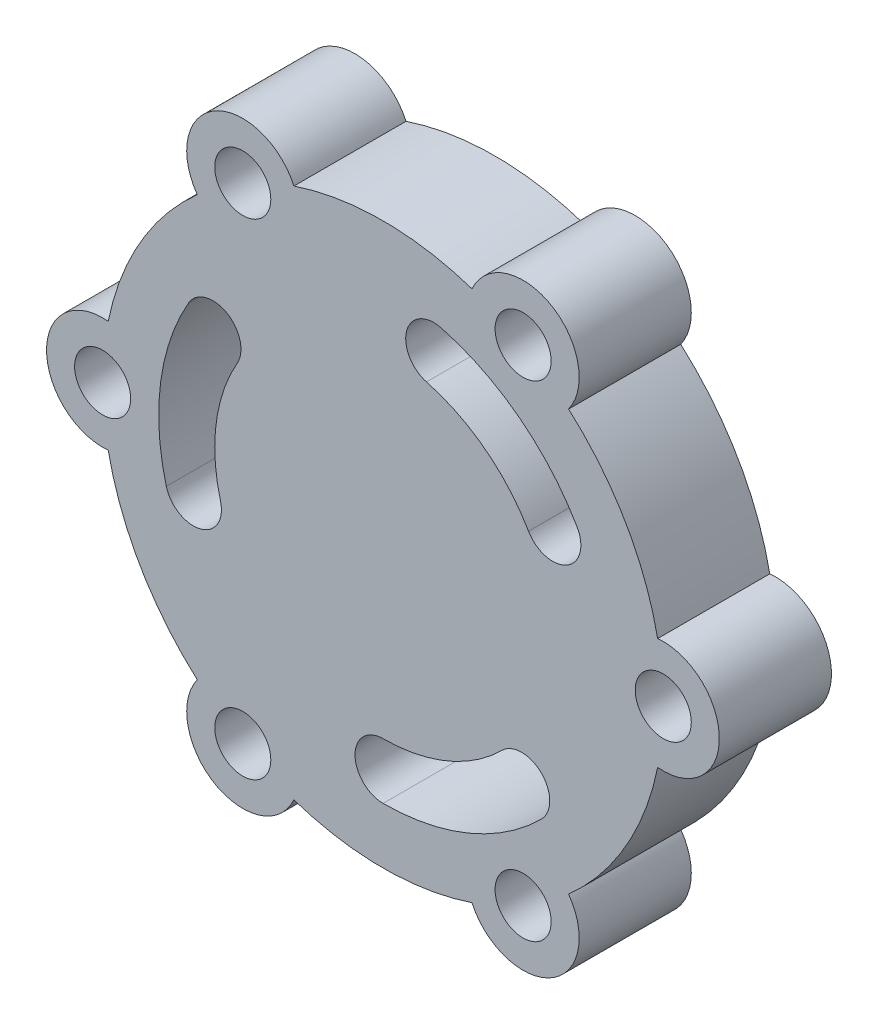
SolidWorks part; units mm, degrees
ref_plane "Front Plane" through (0, 0, 0) normal (0, 0, 1) x (1, 0, 0)
ref_plane "Top Plane" through (0, 0, 0) normal (0, 1, 0) x (1, 0, 0)
ref_plane "Right Plane" through (0, 0, 0) normal (1, 0, 0) x (0, 0, -1)
sketch "Sketch1" plane through (0, 0, 0) normal (0, 0, 1) x (1, 0, 0)
  line L0 (70, 70) -> (130.598, 105.0412) construction
  line L1 (70, 70) -> (85.4723, 127.7433) construction
  circle A1 centre (120, 70) radius 5
  arc A2 (119, 60.0501) -> (119, 79.9499) centre (120, 70) ccw
  arc A3 (85.8832, 22.5898) -> (103.1168, 32.5397) centre (95, 26.6987) ccw
  circle A4 centre (95, 26.6987) radius 5
  arc A5 (36.8832, 32.5397) -> (54.1168, 22.5898) centre (45, 26.6987) ccw
  circle A6 centre (45, 26.6987) radius 5
  arc A7 (21, 79.9499) -> (21, 60.0501) centre (20, 70) ccw
  circle A8 centre (20, 70) radius 5
  arc A9 (54.1168, 117.4102) -> (36.8832, 107.4603) centre (45, 113.3013) ccw
  circle A10 centre (45, 113.3013) radius 5
  arc A11 (103.1168, 107.4603) -> (85.8832, 117.4102) centre (95, 113.3013) ccw
  circle A12 centre (95, 113.3013) radius 5
  arc A13 (36.8832, 107.4603) -> (21, 79.9499) centre (70, 70) ccw
  circle A14 centre (70, 70) radius 35 construction
  arc A15 (21, 60.0501) -> (36.8832, 32.5397) centre (70, 70) ccw
  arc A16 (100.299, 87.5206) -> (79.0587, 103.8074) centre (70, 70) ccw construction
  arc A17 (54.1168, 22.5898) -> (85.8832, 22.5898) centre (70, 70) ccw
  arc A18 (104.6274, 90.0235) -> (80.3528, 108.637) centre (70, 70) ccw
  arc A19 (103.1168, 32.5397) -> (119, 60.0501) centre (70, 70) ccw
  arc A20 (95.9706, 85.0176) -> (77.7646, 98.9778) centre (70, 70) ccw
  arc A21 (119, 79.9499) -> (103.1168, 107.4603) centre (70, 70) ccw
  arc A22 (95.9706, 85.0176) -> (104.6274, 90.0235) centre (100.299, 87.5206) ccw
  arc A23 (85.8832, 117.4102) -> (54.1168, 117.4102) centre (70, 70) ccw
  arc A24 (80.3528, 108.637) -> (77.7646, 98.9778) centre (79.0587, 103.8074) ccw
  arc A25 (70.0204, 40) -> (91.2132, 48.7868) centre (70, 70) ccw
  arc A26 (70.0204, 40) -> (70.0272, 30) centre (70.0238, 35) ccw
  arc A27 (98.2843, 41.7157) -> (91.2132, 48.7868) centre (94.7487, 45.2513) ccw
  arc A28 (70.0272, 30) -> (98.2843, 41.7157) centre (70, 70) ccw
  arc A29 (70.0238, 35) -> (94.7487, 45.2513) centre (70, 70) ccw construction
  arc A30 (44.0091, 84.9824) -> (41.0222, 62.2354) centre (70, 70) ccw
  arc A31 (44.0091, 84.9824) -> (35.3454, 89.9765) centre (39.6772, 87.4794) ccw
  arc A32 (31.363, 59.6472) -> (41.0222, 62.2354) centre (36.1926, 60.9413) ccw
  arc A33 (35.3454, 89.9765) -> (31.363, 59.6472) centre (70, 70) ccw
  arc A34 (39.6772, 87.4794) -> (36.1926, 60.9413) centre (70, 70) ccw construction
  point P17 (91.2972, 97.7746)
  point P24 (70, 70)
  point P42 (83.4049, 37.6688)
  point P49 (35.2979, 74.5566)
  point P54 (70, 70)
  dimension "D3" = 3
  dimension "D4" = 20
  dimension "D5" = 10
  dimension "D1" = 70
  dimension "D2" = 70
  dimension "D6" = 6
extrude "Boss-Extrude1" add sketch "Sketch1" along normal blind 20
